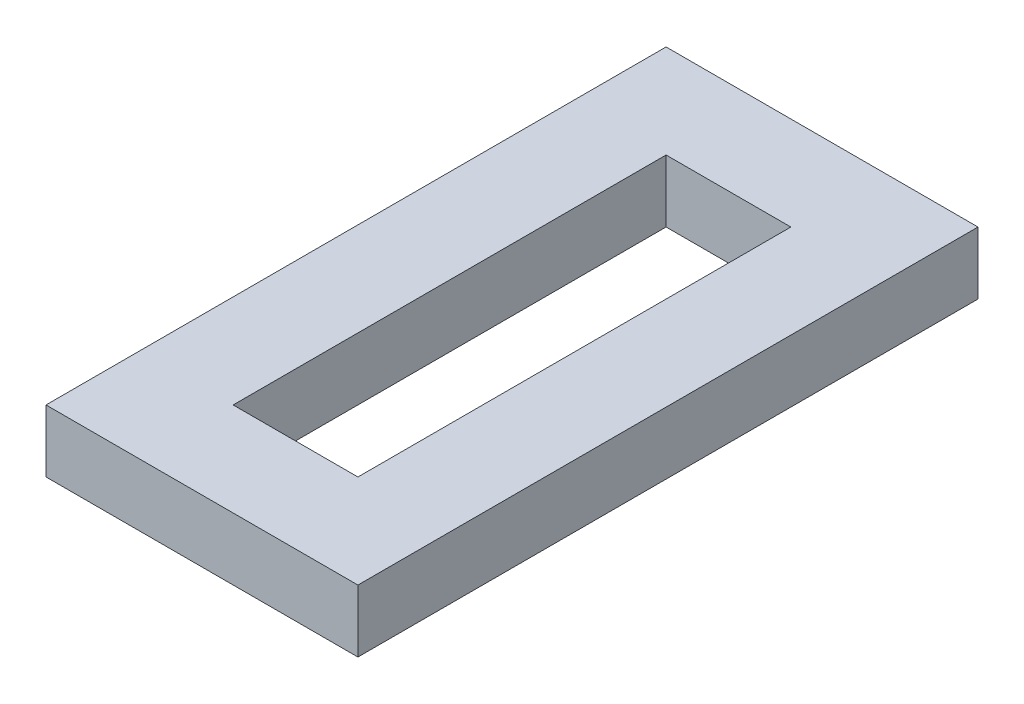
SolidWorks part; units mm, degrees
ref_plane "Front Plane" through (0, 0, 0) normal (0, 0, 1) x (1, 0, 0)
ref_plane "Top Plane" through (0, 0, 0) normal (0, 1, 0) x (1, 0, 0)
ref_plane "Right Plane" through (0, 0, 0) normal (1, 0, 0) x (0, 0, -1)
sketch "Sketch1" plane through (0, 0, 0) normal (0, 1, 0) x (1, 0, 0)
  line L0 (-10, -34.7) -> (10, -34.7)
  line L1 (-25, -49.7) -> (25, -49.7)
  line L2 (-25, -49.7) -> (-25, 49.7)
  line L3 (-25, 49.7) -> (25, 49.7)
  line L4 (25, -49.7) -> (25, 49.7)
  line L5 (10, -34.7) -> (10, 34.7)
  line L6 (-10, 34.7) -> (10, 34.7)
  line L7 (-10, -34.7) -> (-10, 34.7)
  point P0 (0, 0)
  dimension "D1" = 50
  dimension "D2" = 99.4
  dimension "D3" = 15
extrude "Boss-Extrude1" add sketch "Sketch1" against normal blind 10
